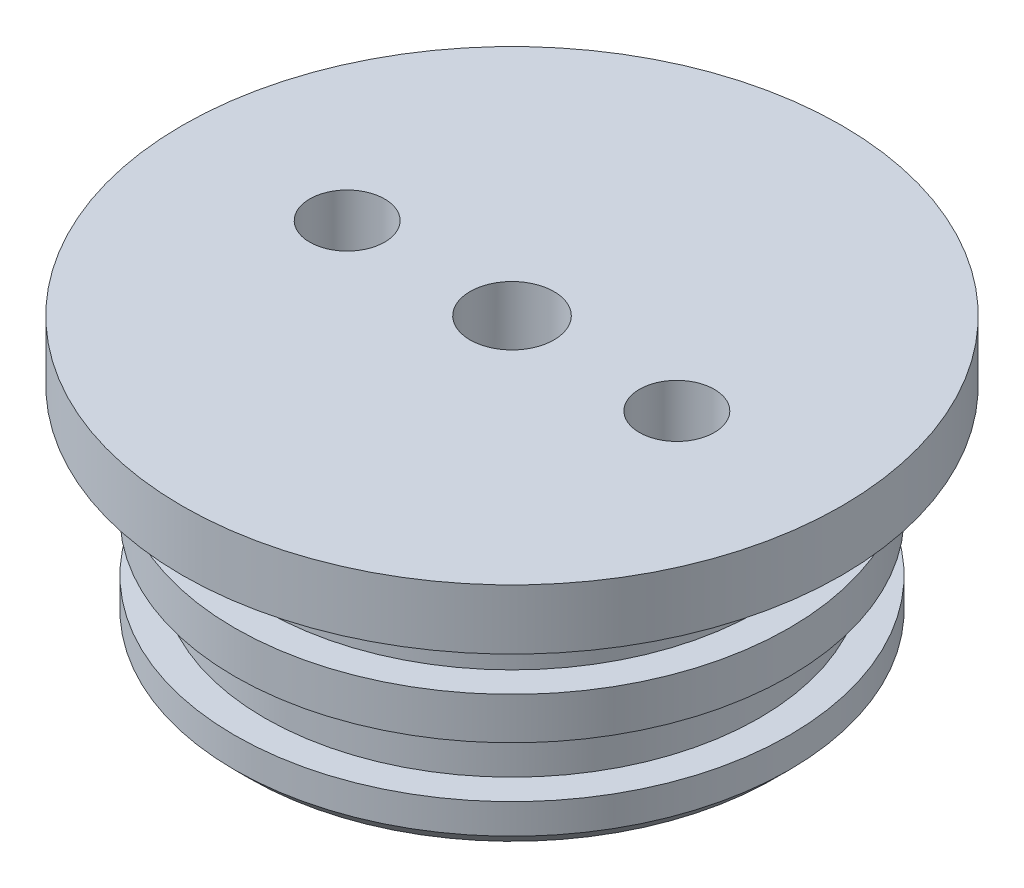
SolidWorks part; units mm, degrees
ref_plane "前视基准面" through (0, 0, 0) normal (0, 0, 1) x (1, 0, 0)
ref_plane "上视基准面" through (0, 0, 0) normal (0, 1, 0) x (1, 0, 0)
ref_plane "右视基准面" through (0, 0, 0) normal (1, 0, 0) x (0, 0, -1)
sketch "草图1" plane through (0, 0, 0) normal (0, 1, 0) x (1, 0, 0)
  circle A0 centre (0, 0) radius 11
  dimension "D1" = 22
extrude "凸台-拉伸1" add sketch "草图1" along normal blind 9
sketch "草图2" plane through (0, 9, 0) normal (0, 1, 0) x (1, 0, 0)
  circle A0 centre (-5.5, 0) radius 0.5
  circle A1 centre (5.5, 0) radius 0.5
  dimension "D1" = 1
  dimension "D2" = 1
  dimension "D3" = 11
  dimension "D4" = 5.5
extrude "切除-拉伸1" cut sketch "草图2" against normal through all
sketch "草图3" plane through (0, 0, 0) normal (0, -1, 0) x (1, 0, 0)
  circle A0 centre (0, 0) radius 9.25
  circle A1 centre (0, 0) radius 16.5491
  dimension "D1" = 18.5
extrude "切除-拉伸2" cut sketch "草图3" against normal blind 7
sketch "草图4" plane through (0, 0, 0) normal (0, 0, 1) x (1, 0, 0)
  line L0 (-9.25, 7) -> (-9.25, 0) construction
  line L1 (-10.25, 6.3) -> (-8.25, 6.3)
  line L2 (-10.25, 6.3) -> (-10.25, 4.6)
  line L3 (-10.25, 4.6) -> (-8.25, 4.6)
  line L4 (-8.25, 6.3) -> (-8.25, 4.6)
  line L5 (-10.25, 6.3) -> (-8.25, 4.6) construction
  line L6 (-10.25, 4.6) -> (-8.25, 6.3) construction
  line L7 (-9.25, 0) -> (9.25, 0) construction
  line L8 (-10.25, 3.2) -> (-8.25, 3.2)
  line L9 (-10.25, 3.2) -> (-10.25, 1.5)
  line L10 (-10.25, 1.5) -> (-8.25, 1.5)
  line L11 (-8.25, 3.2) -> (-8.25, 1.5)
  line L12 (-10.25, 3.2) -> (-8.25, 1.5) construction
  line L13 (-10.25, 1.5) -> (-8.25, 3.2) construction
  line L14 (0, 0) -> (0, 12.2991) construction
  point P0 (-9.25, 5.45)
  point P7 (-9.25, 2.35)
  dimension "D1" = 1.7
  dimension "D2" = 1.7
  dimension "D3" = 1.5
  dimension "D4" = 1.4
  dimension "D5" = 2
  dimension "D6" = 2
revolve "切除-旋转1" cut sketch "草图4" angle 360 about L14
sketch "草图5" plane through (0, 0, 0) normal (0, -1, 0) x (1, 0, 0)
  line L1 (-2.5, 3) -> (2.5, 3)
  line L2 (-2.5, 3) -> (-2.5, -3)
  line L3 (-2.5, -3) -> (2.5, -3)
  line L4 (2.5, 3) -> (2.5, -3)
  line L5 (-2.5, 3) -> (2.5, -3) construction
  line L6 (-2.5, -3) -> (2.5, 3) construction
  point P0 (0, 0)
  dimension "D1" = 6
  dimension "D2" = 5
extrude "切除-拉伸3" cut sketch "草图5" against normal blind 7
sketch "草图6" plane through (0, 9, 0) normal (0, 1, 0) x (1, 0, 0)
  circle A0 centre (0, 0) radius 1.4
  dimension "D1" = 2.8
extrude "切除-拉伸4" cut sketch "草图6" against normal blind 7
sketch "草图7" plane through (0, 9, 0) normal (0, 1, 0) x (1, 0, 0)
  circle A0 centre (-5.5, 0) radius 1.25
  circle A1 centre (5.5, 0) radius 1.25
  dimension "D1" = 2.5
  dimension "D2" = 2.5
extrude "切除-拉伸5" cut sketch "草图7" against normal blind 2.5
sketch "草图8" plane through (0, 0, 0) normal (0, -1, 0) x (1, 0, 0)
  circle A0 centre (-5.5, 0) radius 1.25
  circle A1 centre (5.5, 0) radius 1.25
  dimension "D1" = 2.5
  dimension "D2" = 2.5
extrude "切除-拉伸6" cut sketch "草图8" against normal blind 1.5
sketch "草图9" plane through (0, 0, 0) normal (0, -1, 0) x (1, 0, 0)
  line L0 (-2.5, 3) -> (-2.5, -3) construction
  line L1 (2.5, 3) -> (-2.5, 3) construction
  line L2 (2.5, -3) -> (2.5, 3) construction
  line L4 (-2.5, -3) -> (2.5, -3) construction
  line L5 (-2.5, -3) -> (2.5, -3)
  line L6 (2.5, -3) -> (2.5, 3)
  line L7 (2.5, 3) -> (-2.5, 3)
  line L8 (-2.5, 3) -> (-2.5, -3)
  line L9 (3.5, 4) -> (-3.5, 4)
  line L10 (-3.5, 4) -> (-3.5, -4)
  line L11 (-3.5, -4) -> (3.5, -4)
  line L12 (3.5, -4) -> (3.5, 4)
  circle A1 centre (0, 0) radius 9.25
  circle A10 centre (0, 0) radius 9.25
  line M5 (-2.5, 3) -> (2.5, 3)
  line M6 (2.5, 3) -> (2.5, -3)
  line M7 (2.5, -3) -> (-2.5, -3)
  line M8 (-2.5, -3) -> (-2.5, 3)
  dimension "D1" = 0
  dimension "D2" = 1
extrude "切除-拉伸7" cut sketch "草图9" against normal blind 2 contours L11 L12 L9 L10 M8 M5 M6 M7
chamfer "倒角1" distance 0.5 angle 45 1 edges at (0, 0, -9.25)
